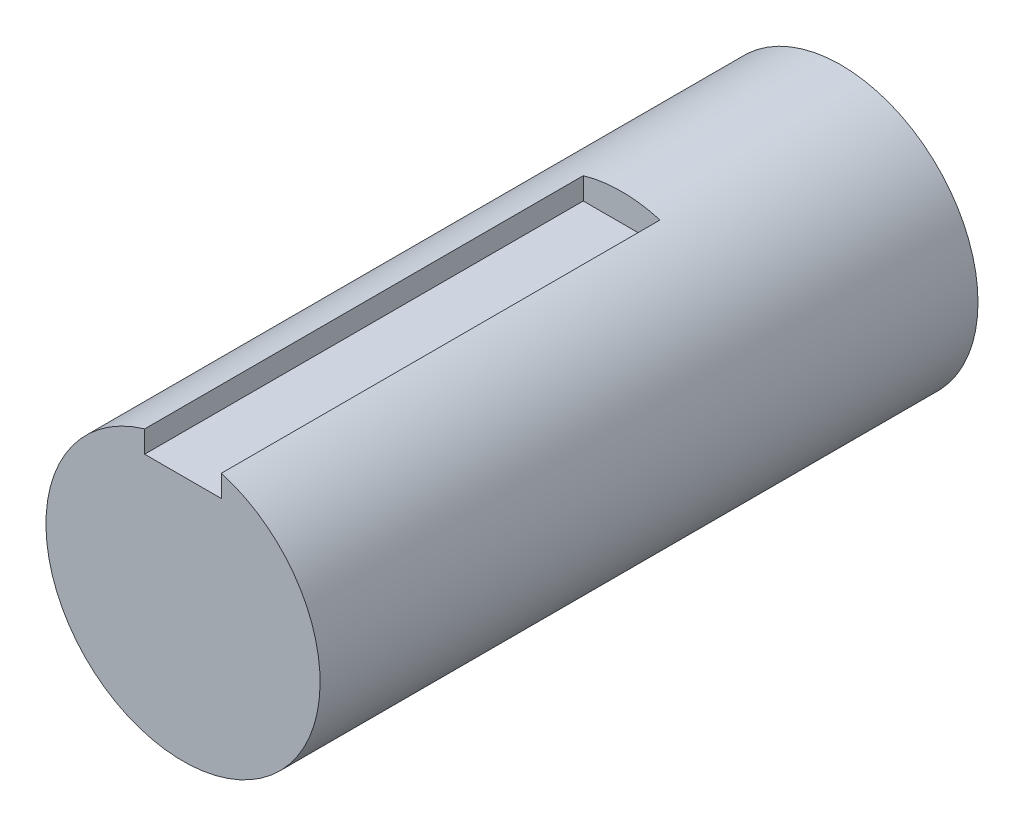
SolidWorks part; units mm, degrees
ref_plane "Front Plane" through (0, 0, 0) normal (0, 0, 1) x (1, 0, 0)
ref_plane "Top Plane" through (0, 0, 0) normal (0, 1, 0) x (1, 0, 0)
ref_plane "Right Plane" through (0, 0, 0) normal (1, 0, 0) x (0, 0, -1)
sketch "Sketch1" plane through (0, 0, 0) normal (0, 0, 1) x (1, 0, 0)
  circle A0 centre (0, 0) radius 25
  dimension "D1" = 50
extrude "Boss-Extrude1" add sketch "Sketch1" along normal mid plane 120
sketch "Sketch2" plane through (0, 0, 60) normal (0, 0, 1) x (1, 0, 0)
  line L0 (0, -55) -> (0, 55) construction
  line L1 (-7, 30) -> (7, 30)
  line L2 (-7, 30) -> (-7, 20)
  line L3 (-7, 20) -> (7, 20)
  line L4 (7, 30) -> (7, 20)
  line L5 (-7, 30) -> (7, 20) construction
  line L6 (-7, 20) -> (7, 30) construction
  circle A0 centre (0, 0) radius 25 construction
  point P0 (0, 25)
  dimension "D1" = 14
  dimension "D2" = 10
extrude "Cut-Extrude1" cut sketch "Sketch2" against normal blind 80
